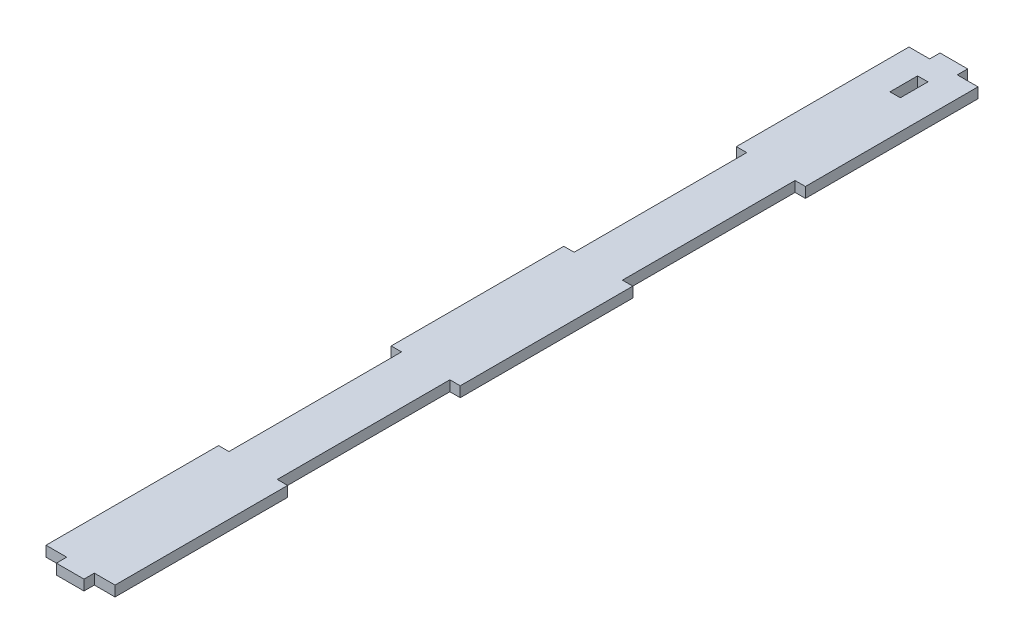
SolidWorks part; units mm, degrees
ref_plane "Alzado" through (0, 0, 0) normal (0, 0, 1) x (1, 0, 0)
ref_plane "Planta" through (0, 0, 0) normal (0, 1, 0) x (1, 0, 0)
ref_plane "Vista lateral" through (0, 0, 0) normal (1, 0, 0) x (0, 0, -1)
sketch "Croquis1" plane through (0, 0, 0) normal (0, 1, 0) x (1, 0, 0)
  line L0 (14, 250) -> (20, 250)
  line L1 (20, 100) -> (20, 150)
  line L2 (0, 0) -> (6, 0)
  line L3 (0, 150) -> (0, 100)
  line L4 (20, 125) -> (20, 150)
  line L5 (20, 150) -> (17, 150)
  line L6 (17, 150) -> (17, 200)
  line L7 (17, 200) -> (20, 200)
  line L8 (20, 200) -> (20, 250)
  line L9 (0, 250) -> (0, 200)
  line L11 (20, 200) -> (20, 250)
  line L12 (14, 0) -> (20, 0)
  line L13 (3, 200) -> (3, 150)
  line L14 (17, 50) -> (20, 50)
  line L15 (17, 100) -> (17, 50)
  line L16 (20, 100) -> (17, 100)
  line L17 (3, 150) -> (0, 150)
  line L18 (10, 253) -> (10, 240)
  line L19 (0, 200) -> (3, 200)
  line L20 (0, 100) -> (3, 100)
  line L21 (3, 250) -> (0, 250)
  line L22 (3, 100) -> (3, 50)
  line L23 (3, 50) -> (0, 50)
  line L24 (0, 50) -> (0, 0)
  line L27 (20, 50) -> (20, 0)
  line L28 (10, 253) -> (6, 253)
  line L32 (6, 253) -> (6, 250)
  line L33 (14, -3) -> (6, -3)
  line L34 (6, -3) -> (6, 0)
  line L35 (14, -3) -> (14, 0)
  line L37 (10, 253) -> (14, 253)
  line L38 (14, 253) -> (14, 250)
  line L39 (6, 250) -> (3, 250)
  line L40 (10, 240) -> (10, 244)
  line L41 (10, 244) -> (8.5, 244)
  line L42 (8.5, 244) -> (8.5, 236)
  line L43 (8.5, 236) -> (11.5, 236)
  line L44 (11.5, 236) -> (11.5, 244)
  line L45 (11.5, 244) -> (10, 244)
  dimension "D2" = 50
  dimension "D4" = 13
  dimension "D5" = 3
  dimension "D6" = 50
  dimension "D7" = 50
  dimension "D8" = 3
  dimension "D9" = 4
  dimension "D10" = 1.5
  dimension "D11" = 8
  dimension "D12" = 3
extrude "Saliente-Extruir1" add sketch "Croquis1" along normal blind 3
